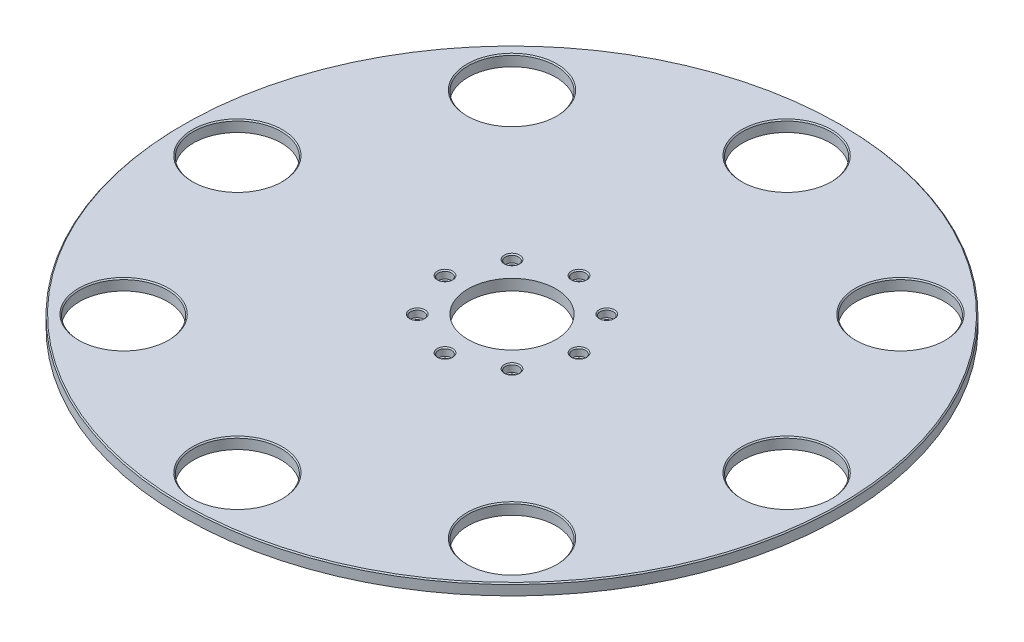
SolidWorks part; units mm, degrees
ref_plane "Front Plane" through (0, 0, 0) normal (0, 0, 1) x (1, 0, 0)
ref_plane "Top Plane" through (0, 0, 0) normal (0, 1, 0) x (1, 0, 0)
ref_plane "Right Plane" through (0, 0, 0) normal (1, 0, 0) x (0, 0, -1)
sketch "Sketch2" plane through (0, 0, 0) normal (0, 1, 0) x (1, 0, 0)
  line L0 (0, 409.7546) -> (0, -366.7272) construction
  line L1 (-380.7051, 0) -> (447.7899, 0) construction
  circle A0 centre (0, 0) radius 300
  circle A1 centre (0, 0) radius 40
  circle A2 centre (0, 250) radius 40
  circle A3 centre (176.7767, 176.7767) radius 40
  circle A4 centre (250, 0) radius 40
  circle A5 centre (176.7767, -176.7767) radius 40
  circle A6 centre (0, -250) radius 40
  circle A7 centre (-176.7767, -176.7767) radius 40
  circle A8 centre (-250, 0) radius 40
  circle A9 centre (-176.7767, 176.7767) radius 40
  point P26 (0, 0)
  point P52 (0, 0)
  dimension "D1" = 250
  dimension "D2" = 80
  dimension "D3" = 80
  dimension "D5" = 600
  dimension "D4" = 8
extrude "Boss-Extrude10" add sketch "Sketch2" along normal blind 10
chamfer "Chamfer1" distance 1 angle 45 9 edges at (-176.7767, 10, 216.7767) (0, 10, 290) (176.7767, 10, 216.7767) (250, 10, 40) (176.7767, 10, -136.7767) (0, 10, -210) (-176.7767, 10, -136.7767) (-250, 10, 40) (0, 10, 300)
sketch "Sketch13" plane through (0, 10, 0) normal (0, 1, 0) x (1, 0, 0)
  line L0 (0, 0) -> (-373.6419, 0) construction
  circle A0 centre (-61, 0) radius 6
  circle A1 centre (-43.1335, 43.1335) radius 6
  circle A2 centre (0, 61) radius 6
  circle A3 centre (43.1335, 43.1335) radius 6
  circle A4 centre (61, 0) radius 6
  circle A5 centre (43.1335, -43.1335) radius 6
  circle A6 centre (0, -61) radius 6
  circle A7 centre (-43.1335, -43.1335) radius 6
  point P21 (0, 0)
  dimension "D1" = 61
  dimension "D2" = 12
  dimension "D3" = 8
extrude "Cut-Extrude1" cut sketch "Sketch13" against normal blind 7
sketch "Sketch14" plane through (0, 0, 0) normal (0, -1, 0) x (1, 0, 0)
  line L0 (0, 0) -> (-132.8482, 0) construction
  circle A0 centre (-61, 0) radius 4
  circle A1 centre (-43.1335, 43.1335) radius 4
  circle A2 centre (0, 61) radius 4
  circle A3 centre (43.1335, 43.1335) radius 4
  circle A4 centre (61, 0) radius 4
  circle A5 centre (43.1335, -43.1335) radius 4
  circle A6 centre (0, -61) radius 4
  circle A7 centre (-43.1335, -43.1335) radius 4
  point P21 (0, 0)
  dimension "D1" = 61
  dimension "D2" = 8
  dimension "D3" = 8
chamfer "Chamfer2" distance 1 angle 45 8 edges at (0, 10, 67) (43.1335, 10, 49.1335) (61, 10, 6) (43.1335, 10, -37.1335) (0, 10, -55) (-43.1335, 10, -37.1335) (-61, 10, 6) (-43.1335, 10, 49.1335)
extrude "Cut-Extrude2" cut sketch "Sketch14" against normal blind 3
